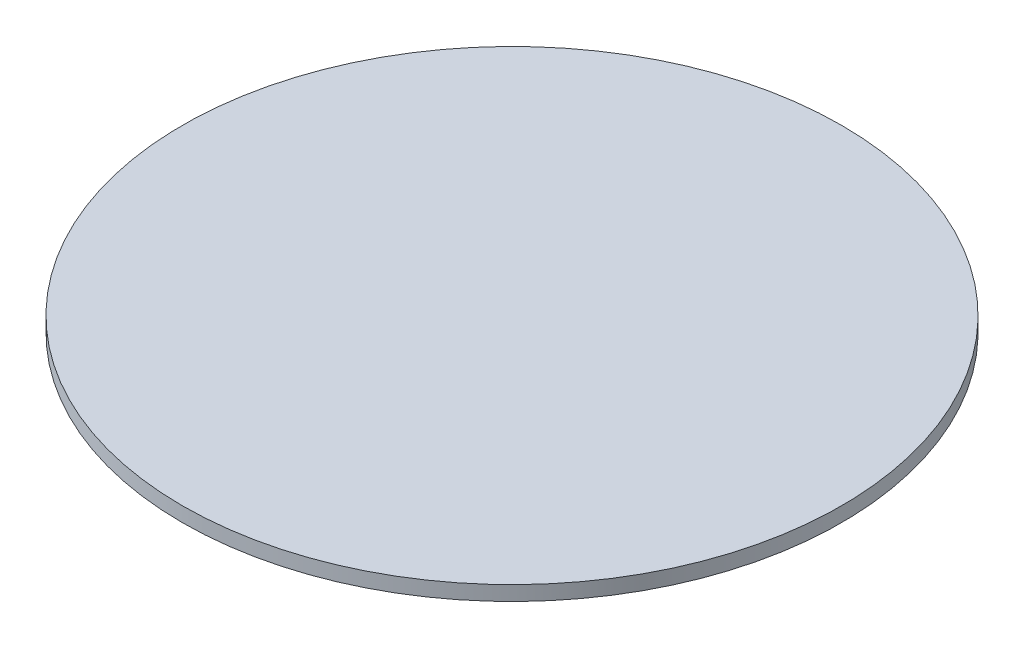
SolidWorks part; units mm, degrees
ref_plane "Front Plane" through (0, 0, 0) normal (0, 0, 1) x (1, 0, 0)
ref_plane "Top Plane" through (0, 0, 0) normal (0, 1, 0) x (1, 0, 0)
ref_plane "Right Plane" through (0, 0, 0) normal (1, 0, 0) x (0, 0, -1)
sketch "Sketch2" plane through (0, 0, 0) normal (0, 1, 0) x (1, 0, 0)
  circle A0 centre (0, 0) radius 45
extrude "Boss-Extrude1" add sketch "Sketch2" along normal blind 2 contours A0
